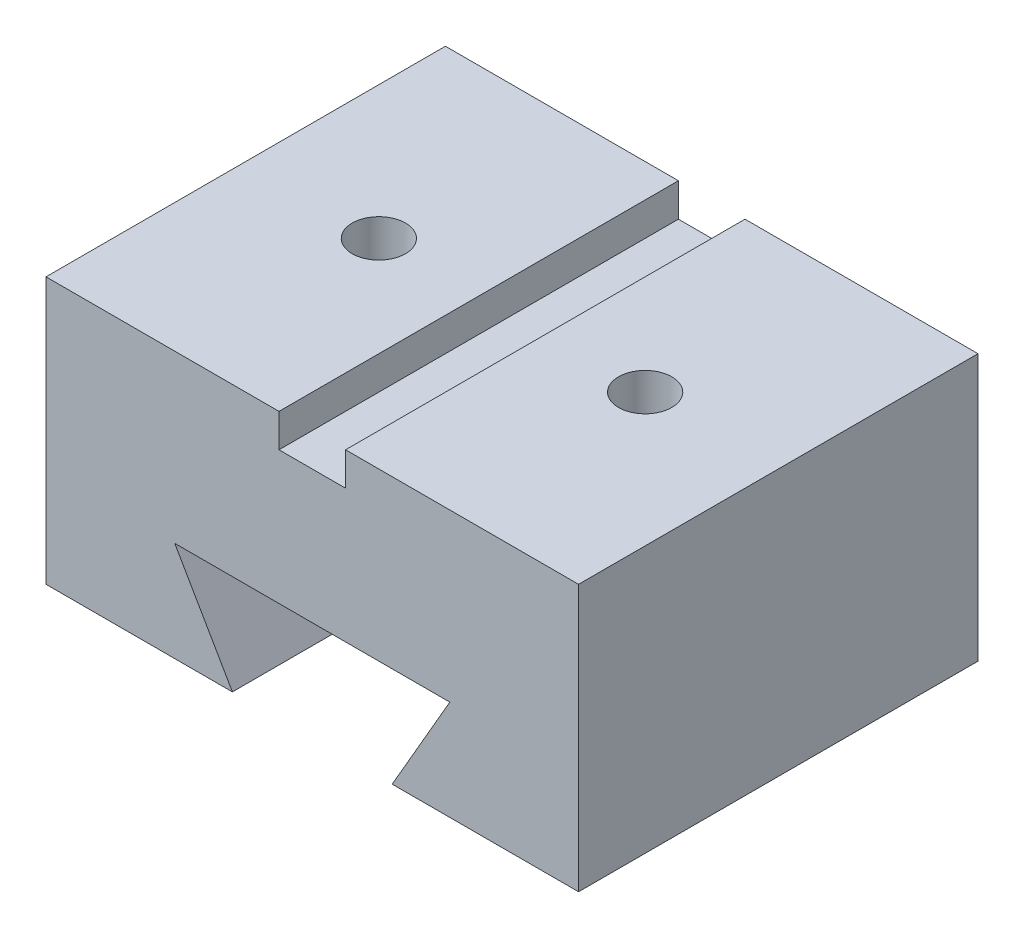
SolidWorks part; units mm, degrees
ref_plane "前视基准面" through (0, 0, 0) normal (0, 0, 1) x (1, 0, 0)
ref_plane "上视基准面" through (0, 0, 0) normal (0, 1, 0) x (1, 0, 0)
ref_plane "右视基准面" through (0, 0, 0) normal (1, 0, 0) x (0, 0, -1)
sketch "草图1" plane through (0, 0, 0) normal (0, 1, 0) x (1, 0, 0)
  line L0 (-40, 30) -> (40, 30)
  line L1 (40, 30) -> (40, -30)
  line L2 (40, -30) -> (-40, -30)
  line L3 (-40, -30) -> (-40, 30)
extrude "凸台-拉伸1" add sketch "草图1" along normal blind 40
sketch "草图2" plane through (0, 0, 0) normal (0, 0, 1) x (1, 0, 0)
  line L0 (-12, 0) -> (12, 0)
  line L1 (12, 0) -> (20.6603, 15)
  line L2 (20.6603, 15) -> (-20.6603, 15)
  line L3 (-20.6603, 15) -> (-12, 0)
extrude "切除-拉伸1" cut sketch "草图2" along normal through all
sketch "草图3" plane through (0, 0, 0) normal (0, 0, 1) x (1, 0, 0)
  line L0 (-12, 0) -> (12, 0)
  line L1 (12, 0) -> (20.6603, 15)
  line L2 (20.6603, 15) -> (-20.6603, 15)
  line L3 (-20.6603, 15) -> (-12, 0)
extrude "切除-拉伸2" cut sketch "草图3" against normal through all
ref_plane "基准面1" through (0, 40, 0) normal (0, 1, 0) x (1, 0, 0)
sketch "草图4" plane through (0, 40, 0) normal (0, 1, 0) x (1, 0, 0)
  line L0 (-5, 30) -> (5, 30)
  line L1 (5, 30) -> (5, -30)
  line L2 (5, -30) -> (-5, -30)
  line L3 (-5, -30) -> (-5, 30)
extrude "切除-拉伸3" cut sketch "草图4" against normal blind 5
sketch "草图5" plane through (0, 40, 0) normal (0, 1, 0) x (1, 0, 0)
  circle A0 centre (-20, 0) radius 4
  circle A1 centre (20, 0) radius 4
extrude "切除-拉伸4" cut sketch "草图5" against normal blind 12
